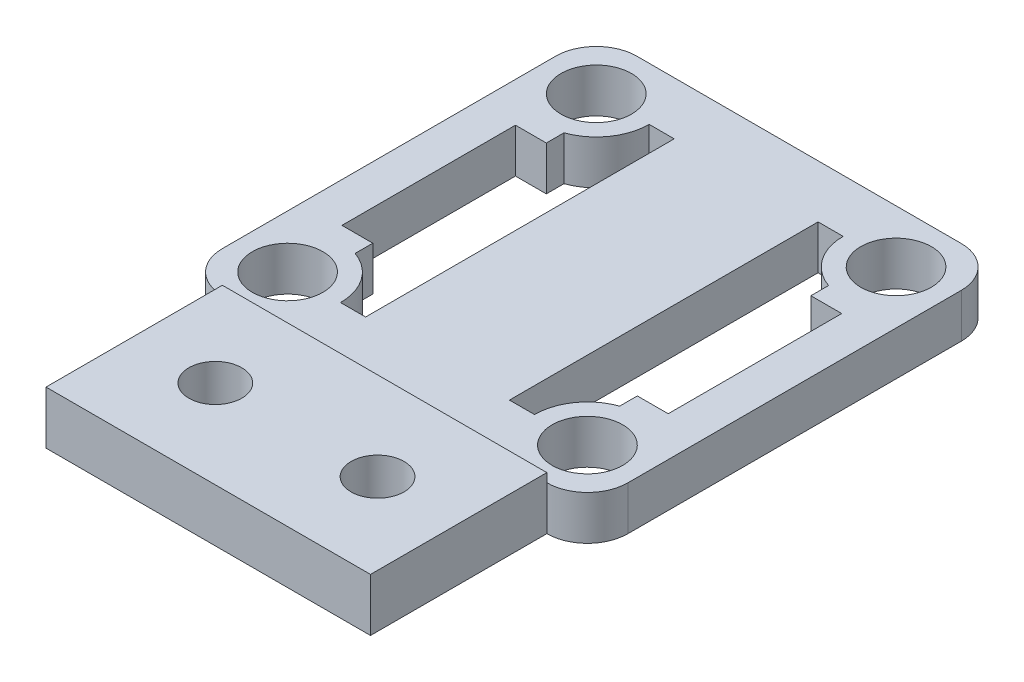
SolidWorks part; units mm, degrees
ref_plane "Front Plane" through (0, 0, 0) normal (0, 0, 1) x (1, 0, 0)
ref_plane "Top Plane" through (0, 0, 0) normal (0, 1, 0) x (1, 0, 0)
ref_plane "Right Plane" through (0, 0, 0) normal (1, 0, 0) x (0, 0, -1)
sketch "Sketch1" plane through (0, 0, 0) normal (0, 1, 0) x (1, 0, 0)
  line L1 (-12.6491, 14.6331) -> (5.7509, 14.6331)
  line L2 (-14.9491, 12.3331) -> (-14.9491, -6.5669)
  line L3 (-12.6491, -8.8669) -> (5.7509, -8.8669)
  line L4 (8.0509, 12.3331) -> (8.0509, -6.5669)
  line L5 (-14.9491, 14.6331) -> (8.0509, -8.8669) construction
  line L6 (-14.9491, -8.8669) -> (8.0509, 14.6331) construction
  arc A0 (8.0509, 12.3331) -> (5.7509, 14.6331) centre (5.7509, 12.3331) ccw
  arc A1 (-12.6491, -8.8669) -> (-14.9491, -6.5669) centre (-12.6491, -6.5669) cw
  arc A2 (5.7509, -8.8669) -> (8.0509, -6.5669) centre (5.7509, -6.5669) ccw
  arc A3 (-14.9491, 12.3331) -> (-12.6491, 14.6331) centre (-12.6491, 12.3331) cw
  point P0 (-3.4491, 2.8831)
  dimension "D3" = 2.3
  dimension "D4" = 2.3
  dimension "D1" = 23.5
  dimension "D2" = 23
extrude "Boss-Extrude1" add sketch "Sketch1" along normal blind 2
sketch "Sketch2" plane through (0, 2, 0) normal (0, 1, 0) x (1, 0, 0)
  line L8 (5.7509, 13.6331) -> (-12.6491, 13.6331)
  line L9 (-13.9491, 12.3331) -> (-13.9491, -6.5669)
  line L10 (-12.6491, -7.8669) -> (5.7509, -7.8669)
  line L11 (7.0509, -6.5669) -> (7.0509, 12.3331)
  line L12 (5.7509, 13.6331) -> (-12.6491, 13.6331)
  line L13 (-13.9491, 12.3331) -> (-13.9491, -6.5669)
  line L14 (-12.6491, -7.8669) -> (5.7509, -7.8669)
  line L15 (7.0509, -6.5669) -> (7.0509, 12.3331)
  arc A8 (7.0509, 12.3331) -> (5.7509, 13.6331) centre (5.7509, 12.3331) ccw
  arc A9 (-12.6491, 13.6331) -> (-13.9491, 12.3331) centre (-12.6491, 12.3331) ccw
  arc A10 (-13.9491, -6.5669) -> (-12.6491, -7.8669) centre (-12.6491, -6.5669) ccw
  arc A11 (5.7509, -7.8669) -> (7.0509, -6.5669) centre (5.7509, -6.5669) ccw
  arc A12 (7.0509, 12.3331) -> (5.7509, 13.6331) centre (5.7509, 12.3331) ccw
  arc A13 (-12.6491, 13.6331) -> (-13.9491, 12.3331) centre (-12.6491, 12.3331) ccw
  arc A14 (-13.9491, -6.5669) -> (-12.6491, -7.8669) centre (-12.6491, -6.5669) ccw
  arc A15 (5.7509, -7.8669) -> (7.0509, -6.5669) centre (5.7509, -6.5669) ccw
  dimension "D1" = 1
extrude "Cut-Extrude2" cut sketch "Sketch2" against normal blind 1
sketch "Sketch5" plane through (0, 1, 0) normal (0, 1, 0) x (1, 0, 0)
  line L0 (-3.4491, 13.6331) -> (-3.4491, -7.8669) construction
  line L1 (5.7509, 13.6331) -> (-12.6491, 13.6331) construction
  line L2 (-12.6491, -7.8669) -> (5.7509, -7.8669) construction
  line L3 (7.0509, 2.8831) -> (-13.9491, 2.8831) construction
  line L4 (7.0509, -6.5669) -> (7.0509, 12.3331) construction
  line L5 (-13.9491, 12.3331) -> (-13.9491, -6.5669) construction
  circle A0 centre (5.0509, 11.6331) radius 2
  circle A1 centre (5.0509, -5.8669) radius 2
  circle A2 centre (-11.9491, -5.8669) radius 2
  circle A3 centre (-11.9491, 11.6331) radius 2
  dimension "D1" = 4
extrude "Cut-Extrude3" cut sketch "Sketch5" against normal through all
sketch "Sketch6" plane through (0, 1, 0) normal (0, 1, 0) x (1, 0, 0)
  line L0 (-14.9491, 12.3331) -> (-14.9491, -6.5669) construction
  line L1 (8.0509, -6.5669) -> (8.0509, 12.3331) construction
  line L14 (4.0509, -5.8669) -> (4.0509, 11.6331)
  line L15 (4.0509, -3.0385) -> (4.0509, 8.8047)
  line L16 (2.0509, 11.6331) -> (2.0509, -5.8669)
  line L17 (-10.9491, 12.3331) -> (-10.9491, -6.5669)
  line L18 (-10.9491, 8.8047) -> (-10.9491, -3.0385)
  line L19 (-8.9491, 11.6331) -> (-8.9491, -5.8669)
  arc A5 (-11.9491, -8.8669) -> (-14.9491, -5.8669) centre (-11.9491, -5.8669) ccw
  arc A6 (-8.9491, -5.8669) -> (-10.9491, -3.0385) centre (-11.9491, -5.8669) ccw
  arc A20 (5.0509, 14.6331) -> (8.0509, 11.6331) centre (5.0509, 11.6331) ccw
  arc A21 (2.0509, 11.6331) -> (4.0509, 8.8047) centre (5.0509, 11.6331) ccw
  arc A23 (-14.9491, 11.6331) -> (-11.9491, 14.6331) centre (-11.9491, 11.6331) ccw
  arc A24 (-10.9491, 8.8047) -> (-8.9491, 11.6331) centre (-11.9491, 11.6331) ccw
  arc A26 (8.0509, -5.8669) -> (5.0509, -8.8669) centre (5.0509, -5.8669) ccw
  arc A27 (4.0509, -3.0385) -> (2.0509, -5.8669) centre (5.0509, -5.8669) ccw
  dimension "D1" = 23
  dimension "D2" = 1
  dimension "D3" = 1
  dimension "D4" = 1
  dimension "D5" = 1
  dimension "D6" = 3
  dimension "D7" = 3
extrude "Cut-Extrude4" cut sketch "Sketch6" against normal through all
sketch "Sketch7" plane through (0, 0, 8.8669) normal (0, 0, 1) x (1, 0, 0)
  line L0 (-14.9491, 2) -> (-14.9491, 0) construction
  line L1 (8.0509, 2) -> (8.0509, 0) construction
  line L2 (-12.6491, 2) -> (-12.6491, 0) construction
  line L3 (-12.6491, 1) -> (5.7509, 1)
  line L4 (5.7509, 2) -> (5.7509, 0) construction
  line L5 (5.7509, 1) -> (5.7509, 0)
  line L6 (5.7509, 0) -> (-12.6491, 0)
  line L7 (-12.6491, 0) -> (-12.6491, 1)
  line L8 (-12.6491, 2) -> (5.7509, 2) construction
  dimension "D1" = 23
extrude "Boss-Extrude2" add sketch "Sketch7" along normal blind 10
sketch "Sketch8" plane through (0, 1, 0) normal (0, 1, 0) x (1, 0, 0)
  line L0 (-12.6491, -8.8669) -> (5.7509, -8.8669) construction
  line L1 (-12.6491, -18.8669) -> (-12.6491, -8.8669) construction
  line L2 (5.7509, -18.8669) -> (5.7509, -8.8669) construction
  line L3 (-3.4491, -8.8669) -> (-3.4491, -18.8669) construction
  line L4 (5.7509, -18.8669) -> (-12.6491, -18.8669) construction
  circle A0 centre (1.1509, -13.8669) radius 1.5
  circle A1 centre (-8.0491, -13.8669) radius 1.5
  dimension "D2" = 3
  dimension "D1" = 5
  dimension "D3" = 18.4
  dimension "D4" = 4.6
  dimension "D5" = 4.6
extrude "Cut-Extrude5" cut sketch "Sketch8" against normal through all
sketch "Sketch9" plane through (0, 2, 0) normal (0, 1, 0) x (1, 0, 0)
  line L8 (5.7509, 13.8331) -> (-12.6491, 13.8331)
  line L9 (-14.1491, 12.3331) -> (-14.1491, -6.5669)
  line L10 (-12.6491, -8.0669) -> (5.7509, -8.0669)
  line L11 (7.2509, -6.5669) -> (7.2509, 12.3331)
  line L12 (5.7509, 13.8331) -> (-12.6491, 13.8331)
  line L13 (-14.1491, 12.3331) -> (-14.1491, -6.5669)
  line L14 (-12.6491, -8.0669) -> (5.7509, -8.0669)
  line L15 (7.2509, -6.5669) -> (7.2509, 12.3331)
  arc A8 (7.2509, 12.3331) -> (5.7509, 13.8331) centre (5.7509, 12.3331) ccw
  arc A9 (-12.6491, 13.8331) -> (-14.1491, 12.3331) centre (-12.6491, 12.3331) ccw
  arc A10 (-14.1491, -6.5669) -> (-12.6491, -8.0669) centre (-12.6491, -6.5669) ccw
  arc A11 (5.7509, -8.0669) -> (7.2509, -6.5669) centre (5.7509, -6.5669) ccw
  arc A12 (7.2509, 12.3331) -> (5.7509, 13.8331) centre (5.7509, 12.3331) ccw
  arc A13 (-12.6491, 13.8331) -> (-14.1491, 12.3331) centre (-12.6491, 12.3331) ccw
  arc A14 (-14.1491, -6.5669) -> (-12.6491, -8.0669) centre (-12.6491, -6.5669) ccw
  arc A15 (5.7509, -8.0669) -> (7.2509, -6.5669) centre (5.7509, -6.5669) ccw
  dimension "D1" = 0.8
extrude "Cut-Extrude6" cut sketch "Sketch9" against normal blind 1
sketch "Sketch11" plane through (0, 1, 0) normal (0, 1, 0) x (1, 0, 0)
  line L0 (-8.9491, 11.6331) -> (-7.528, 11.6331)
  line L1 (-7.528, 11.6331) -> (-7.528, -5.8669)
  line L2 (-7.528, -5.8669) -> (-8.9491, -5.8669)
  line L3 (-8.9491, -5.8669) -> (-8.9491, 11.6331)
  line L4 (-3.4491, 13.8331) -> (-3.4491, -8.0669) construction
  line L5 (5.7509, 13.8331) -> (-12.6491, 13.8331) construction
  line L6 (-12.6491, -8.0669) -> (5.7509, -8.0669) construction
  line L7 (0.6299, -5.8669) -> (2.0509, -5.8669)
  line L8 (0.6299, 11.6331) -> (0.6299, -5.8669)
  line L9 (2.0509, 11.6331) -> (0.6299, 11.6331)
  line L10 (2.0509, -5.8669) -> (2.0509, 11.6331)
  line L11 (-10.9491, 8.8047) -> (-10.9491, -3.0385) construction
  line L12 (-12.6991, 7.8031) -> (-10.9491, 7.8031)
  line L13 (-12.6991, 7.8031) -> (-12.6991, -2.0369)
  line L14 (-12.6991, -2.0369) -> (-10.9491, -2.0369)
  line L15 (-10.9491, 7.8031) -> (-10.9491, -2.0369)
  line L16 (5.8009, -2.0369) -> (4.0509, -2.0369)
  line L17 (4.0509, 7.8031) -> (4.0509, -2.0369)
  line L18 (5.8009, 7.8031) -> (4.0509, 7.8031)
  line L19 (5.8009, 7.8031) -> (5.8009, -2.0369)
  point P22 (-10.9491, 2.8831)
  point P23 (-10.9491, 2.8831)
  dimension "D1" = 9.84
  dimension "D2" = 1.75
extrude "Cut-Extrude7" cut sketch "Sketch11" against normal through all
sketch "Sketch12" plane through (0, 0, 0) normal (0, -1, 0) x (1, 0, 0)
  line L6 (8.0509, -12.3331) -> (8.0509, 6.5669)
  line L7 (5.7509, 8.8669) -> (5.7509, 18.8669)
  line L8 (5.7509, 18.8669) -> (-12.6491, 18.8669)
  line L9 (-12.6491, 18.8669) -> (-12.6491, 8.8669)
  line L10 (-14.9491, 6.5669) -> (-14.9491, -12.3331)
  line L11 (-12.6491, -14.6331) -> (5.7509, -14.6331)
  line L12 (8.0509, -12.3331) -> (8.0509, 6.5669)
  line L13 (5.7509, 8.8669) -> (5.7509, 18.8669)
  line L14 (5.7509, 18.8669) -> (-12.6491, 18.8669)
  line L15 (-12.6491, 18.8669) -> (-12.6491, 8.8669)
  line L16 (-14.9491, 6.5669) -> (-14.9491, -12.3331)
  line L17 (-12.6491, -14.6331) -> (5.7509, -14.6331)
  arc A4 (5.7509, -14.6331) -> (8.0509, -12.3331) centre (5.7509, -12.3331) ccw
  arc A5 (8.0509, 6.5669) -> (5.7509, 8.8669) centre (5.7509, 6.5669) ccw
  arc A6 (-12.6491, 8.8669) -> (-14.9491, 6.5669) centre (-12.6491, 6.5669) ccw
  arc A7 (-14.9491, -12.3331) -> (-12.6491, -14.6331) centre (-12.6491, -12.3331) ccw
  arc A8 (5.7509, -14.6331) -> (8.0509, -12.3331) centre (5.7509, -12.3331) ccw
  arc A9 (8.0509, 6.5669) -> (5.7509, 8.8669) centre (5.7509, 6.5669) ccw
  arc A10 (-12.6491, 8.8669) -> (-14.9491, 6.5669) centre (-12.6491, 6.5669) ccw
  arc A11 (-14.9491, -12.3331) -> (-12.6491, -14.6331) centre (-12.6491, -12.3331) ccw
  dimension "D1" = 0
extrude "Boss-Extrude3" add sketch "Sketch12" along normal blind 2
sketch "Sketch13" plane through (0, 0, 0) normal (0, 1, 0) x (1, 0, 0)
  line L8 (-12.6991, 7.8031) -> (-12.6991, -2.0369)
  line L9 (-12.6991, -2.0369) -> (-10.9491, -2.0369)
  line L10 (-10.9491, -2.0369) -> (-10.9491, -3.0385)
  line L11 (-8.9491, -5.8669) -> (-7.528, -5.8669)
  line L12 (-7.528, -5.8669) -> (-7.528, 11.6331)
  line L13 (-7.528, 11.6331) -> (-8.9491, 11.6331)
  line L14 (-10.9491, 8.8047) -> (-10.9491, 7.8031)
  line L15 (-10.9491, 7.8031) -> (-12.6991, 7.8031)
  line L16 (-12.6991, 7.8031) -> (-12.6991, -2.0369)
  line L17 (-12.6991, -2.0369) -> (-10.9491, -2.0369)
  line L18 (-10.9491, -2.0369) -> (-10.9491, -3.0385)
  line L19 (-8.9491, -5.8669) -> (-7.528, -5.8669)
  line L20 (-7.528, -5.8669) -> (-7.528, 11.6331)
  line L21 (-7.528, 11.6331) -> (-8.9491, 11.6331)
  line L22 (-10.9491, 8.8047) -> (-10.9491, 7.8031)
  line L23 (-10.9491, 7.8031) -> (-12.6991, 7.8031)
  arc A2 (-8.9491, -5.8669) -> (-10.9491, -3.0385) centre (-11.9491, -5.8669) ccw
  arc A3 (-10.9491, 8.8047) -> (-8.9491, 11.6331) centre (-11.9491, 11.6331) ccw
  arc A4 (-8.9491, -5.8669) -> (-10.9491, -3.0385) centre (-11.9491, -5.8669) ccw
  arc A5 (-10.9491, 8.8047) -> (-8.9491, 11.6331) centre (-11.9491, 11.6331) ccw
  dimension "D1" = 0
extrude "Cut-Extrude8" cut sketch "Sketch13" against normal through all both and the other way through all
sketch "Sketch14" plane through (0, 0, 0) normal (0, 1, 0) x (1, 0, 0)
  line L8 (0.6299, -5.8669) -> (2.0509, -5.8669)
  line L9 (4.0509, -3.0385) -> (4.0509, -2.0369)
  line L10 (4.0509, -2.0369) -> (5.8009, -2.0369)
  line L11 (5.8009, -2.0369) -> (5.8009, 7.8031)
  line L12 (5.8009, 7.8031) -> (4.0509, 7.8031)
  line L13 (4.0509, 7.8031) -> (4.0509, 8.8047)
  line L14 (2.0509, 11.6331) -> (0.6299, 11.6331)
  line L15 (0.6299, 11.6331) -> (0.6299, -5.8669)
  line L16 (0.6299, -5.8669) -> (2.0509, -5.8669)
  line L17 (4.0509, -3.0385) -> (4.0509, -2.0369)
  line L18 (4.0509, -2.0369) -> (5.8009, -2.0369)
  line L19 (5.8009, -2.0369) -> (5.8009, 7.8031)
  line L20 (5.8009, 7.8031) -> (4.0509, 7.8031)
  line L21 (4.0509, 7.8031) -> (4.0509, 8.8047)
  line L22 (2.0509, 11.6331) -> (0.6299, 11.6331)
  line L23 (0.6299, 11.6331) -> (0.6299, -5.8669)
  arc A2 (4.0509, -3.0385) -> (2.0509, -5.8669) centre (5.0509, -5.8669) ccw
  arc A3 (2.0509, 11.6331) -> (4.0509, 8.8047) centre (5.0509, 11.6331) ccw
  arc A4 (4.0509, -3.0385) -> (2.0509, -5.8669) centre (5.0509, -5.8669) ccw
  arc A5 (2.0509, 11.6331) -> (4.0509, 8.8047) centre (5.0509, 11.6331) ccw
  dimension "D1" = 0
extrude "Cut-Extrude9" cut sketch "Sketch14" against normal through all both and the other way through all
sketch "Sketch15" plane through (0, 0, 0) normal (0, 1, 0) x (1, 0, 0)
  circle A1 centre (-8.0491, -13.8669) radius 1.5
  circle A2 centre (-8.0491, -13.8669) radius 1.5
  dimension "D1" = 0
extrude "Cut-Extrude10" cut sketch "Sketch15" against normal through all both and the other way through all
sketch "Sketch16" plane through (0, 0, 0) normal (0, 1, 0) x (1, 0, 0)
  circle A1 centre (1.1509, -13.8669) radius 1.5
  circle A2 centre (1.1509, -13.8669) radius 1.5
  dimension "D1" = 0
extrude "Cut-Extrude11" cut sketch "Sketch16" against normal through all both and the other way through all
sketch "Sketch17" plane through (0, 0, 0) normal (0, 1, 0) x (1, 0, 0)
  circle A0 centre (-11.9491, -5.8669) radius 2 construction
  circle A1 centre (5.0509, -5.8669) radius 2 construction
  circle A2 centre (-11.9491, 11.6331) radius 2 construction
  circle A3 centre (5.0509, 11.6331) radius 2 construction
  circle A4 centre (-11.9491, -5.8669) radius 2
  circle A5 centre (5.0509, -5.8669) radius 2
  circle A6 centre (-11.9491, 11.6331) radius 2
  circle A7 centre (5.0509, 11.6331) radius 2
extrude "Cut-Extrude12" cut sketch "Sketch17" against normal through all both and the other way through all
sketch "Sketch18" plane through (0, 1, 0) normal (0, 1, 0) x (1, 0, 0)
  line L4 (5.7509, 13.8331) -> (-12.6491, 13.8331)
  line L5 (-14.1491, 12.3331) -> (-14.1491, -6.5669)
  line L6 (-12.6491, -8.0669) -> (5.7509, -8.0669)
  line L7 (7.2509, -6.5669) -> (7.2509, 12.3331)
  line L8 (5.7509, 13.8331) -> (-12.6491, 13.8331)
  line L9 (-14.1491, 12.3331) -> (-14.1491, -6.5669)
  line L10 (-12.6491, -8.0669) -> (5.7509, -8.0669)
  line L11 (7.2509, -6.5669) -> (7.2509, 12.3331)
  arc A4 (7.2509, 12.3331) -> (5.7509, 13.8331) centre (5.7509, 12.3331) ccw
  arc A5 (-12.6491, 13.8331) -> (-14.1491, 12.3331) centre (-12.6491, 12.3331) ccw
  arc A6 (-14.1491, -6.5669) -> (-12.6491, -8.0669) centre (-12.6491, -6.5669) ccw
  arc A7 (5.7509, -8.0669) -> (7.2509, -6.5669) centre (5.7509, -6.5669) ccw
  arc A8 (7.2509, 12.3331) -> (5.7509, 13.8331) centre (5.7509, 12.3331) ccw
  arc A9 (-12.6491, 13.8331) -> (-14.1491, 12.3331) centre (-12.6491, 12.3331) ccw
  arc A10 (-14.1491, -6.5669) -> (-12.6491, -8.0669) centre (-12.6491, -6.5669) ccw
  arc A11 (5.7509, -8.0669) -> (7.2509, -6.5669) centre (5.7509, -6.5669) ccw
  dimension "D1" = 0
extrude "Boss-Extrude4" add sketch "Sketch18" along normal up to surface (1 mm away) up to face at (-3.4491, 2, -2.8831)
sketch "Sketch19" plane through (0, 1, 0) normal (0, -1, 0) x (1, 0, 0)
  line L8 (-10.9491, 3.0385) -> (-10.9491, 2.0369)
  line L9 (-10.9491, 2.0369) -> (-12.6991, 2.0369)
  line L10 (-12.6991, 2.0369) -> (-12.6991, -7.8031)
  line L11 (-12.6991, -7.8031) -> (-10.9491, -7.8031)
  line L12 (-10.9491, -7.8031) -> (-10.9491, -8.8047)
  line L13 (-8.9491, -11.6331) -> (-7.528, -11.6331)
  line L14 (-7.528, -11.6331) -> (-7.528, 5.8669)
  line L15 (-7.528, 5.8669) -> (-8.9491, 5.8669)
  line L16 (-10.9491, 3.0385) -> (-10.9491, 2.0369)
  line L17 (-10.9491, 2.0369) -> (-12.6991, 2.0369)
  line L18 (-12.6991, 2.0369) -> (-12.6991, -7.8031)
  line L19 (-12.6991, -7.8031) -> (-10.9491, -7.8031)
  line L20 (-10.9491, -7.8031) -> (-10.9491, -8.8047)
  line L21 (-8.9491, -11.6331) -> (-7.528, -11.6331)
  line L22 (-7.528, -11.6331) -> (-7.528, 5.8669)
  line L23 (-7.528, 5.8669) -> (-8.9491, 5.8669)
  line L24 (4.0509, 2.0369) -> (4.0509, 3.0385)
  line L25 (2.0509, 5.8669) -> (0.6299, 5.8669)
  line L26 (0.6299, 5.8669) -> (0.6299, -11.6331)
  line L27 (0.6299, -11.6331) -> (2.0509, -11.6331)
  line L28 (4.0509, -8.8047) -> (4.0509, -7.8031)
  line L29 (4.0509, -7.8031) -> (5.8009, -7.8031)
  line L30 (5.8009, -7.8031) -> (5.8009, 2.0369)
  line L31 (5.8009, 2.0369) -> (4.0509, 2.0369)
  line L32 (4.0509, 2.0369) -> (4.0509, 3.0385)
  line L33 (2.0509, 5.8669) -> (0.6299, 5.8669)
  line L34 (0.6299, 5.8669) -> (0.6299, -11.6331)
  line L35 (0.6299, -11.6331) -> (2.0509, -11.6331)
  line L36 (4.0509, -8.8047) -> (4.0509, -7.8031)
  line L37 (4.0509, -7.8031) -> (5.8009, -7.8031)
  line L38 (5.8009, -7.8031) -> (5.8009, 2.0369)
  line L39 (5.8009, 2.0369) -> (4.0509, 2.0369)
  circle A0 centre (5.0509, -11.6331) radius 2 construction
  circle A1 centre (-11.9491, -11.6331) radius 2 construction
  arc A2 (-8.9491, -11.6331) -> (-10.9491, -8.8047) centre (-11.9491, -11.6331) ccw
  arc A3 (-10.9491, 3.0385) -> (-8.9491, 5.8669) centre (-11.9491, 5.8669) ccw
  arc A4 (-8.9491, -11.6331) -> (-10.9491, -8.8047) centre (-11.9491, -11.6331) ccw
  arc A5 (-10.9491, 3.0385) -> (-8.9491, 5.8669) centre (-11.9491, 5.8669) ccw
  arc A6 (2.0509, 5.8669) -> (4.0509, 3.0385) centre (5.0509, 5.8669) ccw
  arc A7 (4.0509, -8.8047) -> (2.0509, -11.6331) centre (5.0509, -11.6331) ccw
  arc A8 (2.0509, 5.8669) -> (4.0509, 3.0385) centre (5.0509, 5.8669) ccw
  arc A9 (4.0509, -8.8047) -> (2.0509, -11.6331) centre (5.0509, -11.6331) ccw
  circle A10 centre (-11.9491, 5.8669) radius 2 construction
  circle A11 centre (5.0509, 5.8669) radius 2 construction
  circle A12 centre (5.0509, -11.6331) radius 2
  circle A13 centre (-11.9491, -11.6331) radius 2
  circle A14 centre (-11.9491, 5.8669) radius 2
  circle A15 centre (5.0509, 5.8669) radius 2
  dimension "D1" = 0
  dimension "D2" = 0
extrude "Cut-Extrude13" cut sketch "Sketch19" against normal through all both and the other way through all
sketch "Sketch20" plane through (0, 2, 0) normal (0, 1, 0) x (1, 0, 0)
  line L4 (5.7509, 14.6331) -> (-12.6491, 14.6331)
  line L5 (-14.9491, 12.3331) -> (-14.9491, -6.5669)
  line L6 (-12.6491, -8.8669) -> (5.7509, -8.8669)
  line L7 (8.0509, -6.5669) -> (8.0509, 12.3331)
  line L8 (5.7509, 14.6331) -> (-12.6491, 14.6331)
  line L9 (-14.9491, 12.3331) -> (-14.9491, -6.5669)
  line L10 (-12.6491, -8.8669) -> (5.7509, -8.8669)
  line L11 (8.0509, -6.5669) -> (8.0509, 12.3331)
  arc A4 (8.0509, 12.3331) -> (5.7509, 14.6331) centre (5.7509, 12.3331) ccw
  arc A5 (-12.6491, 14.6331) -> (-14.9491, 12.3331) centre (-12.6491, 12.3331) ccw
  arc A6 (-14.9491, -6.5669) -> (-12.6491, -8.8669) centre (-12.6491, -6.5669) ccw
  arc A7 (5.7509, -8.8669) -> (8.0509, -6.5669) centre (5.7509, -6.5669) ccw
  arc A8 (8.0509, 12.3331) -> (5.7509, 14.6331) centre (5.7509, 12.3331) ccw
  arc A9 (-12.6491, 14.6331) -> (-14.9491, 12.3331) centre (-12.6491, 12.3331) ccw
  arc A10 (-14.9491, -6.5669) -> (-12.6491, -8.8669) centre (-12.6491, -6.5669) ccw
  arc A11 (5.7509, -8.8669) -> (8.0509, -6.5669) centre (5.7509, -6.5669) ccw
  dimension "D1" = 0
extrude "Cut-Extrude14" cut sketch "Sketch20" against normal blind 1.5
